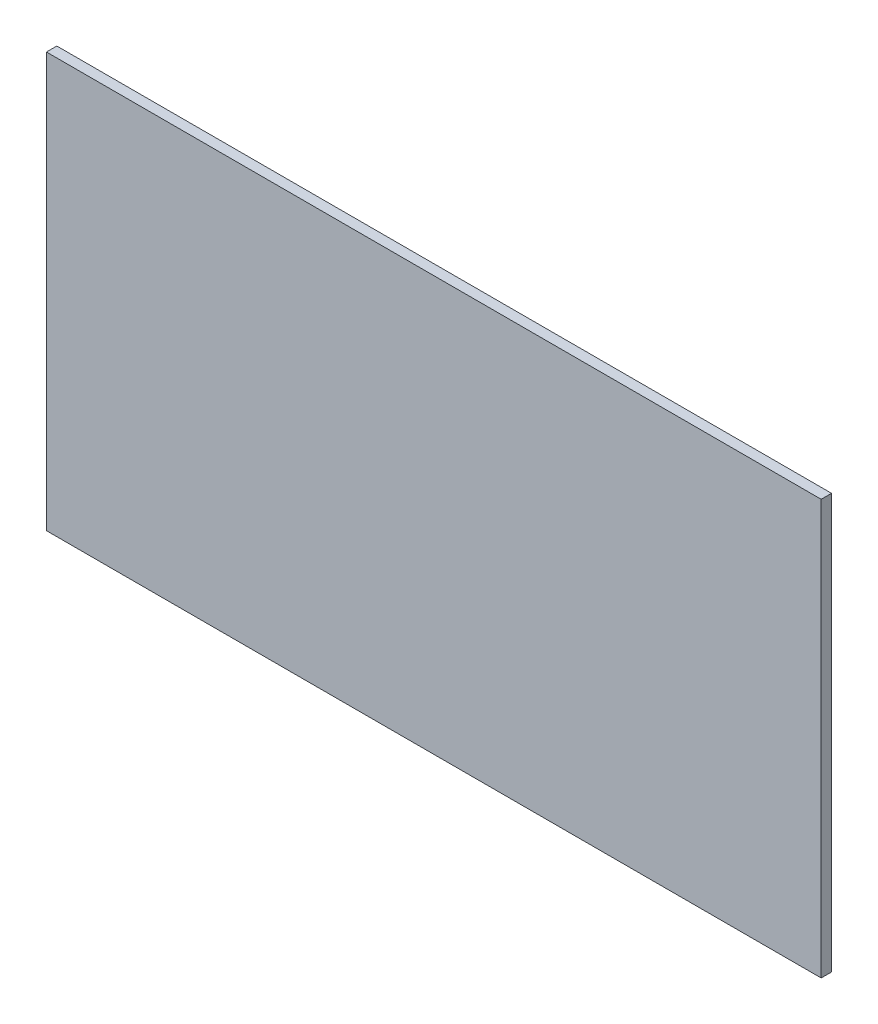
SolidWorks part; units mm, degrees
ref_plane "Спереди" through (0, 0, 0) normal (0, 0, 1) x (1, 0, 0)
ref_plane "Сверху" through (0, 0, 0) normal (0, 1, 0) x (1, 0, 0)
ref_plane "Справа" through (0, 0, 0) normal (1, 0, 0) x (0, 0, -1)
sketch "Эскиз1" plane through (0, 0, 0) normal (0, 1, 0) x (1, 0, 0)
  line L1 (0, 0) -> (186.873, 0)
  line L2 (0, 0) -> (0, -2.5)
  line L3 (0, -2.5) -> (186.873, -2.5)
  line L4 (186.873, 0) -> (186.873, -2.5)
extrude "Вытянуть1" add sketch "Эскиз1" along normal blind 100
